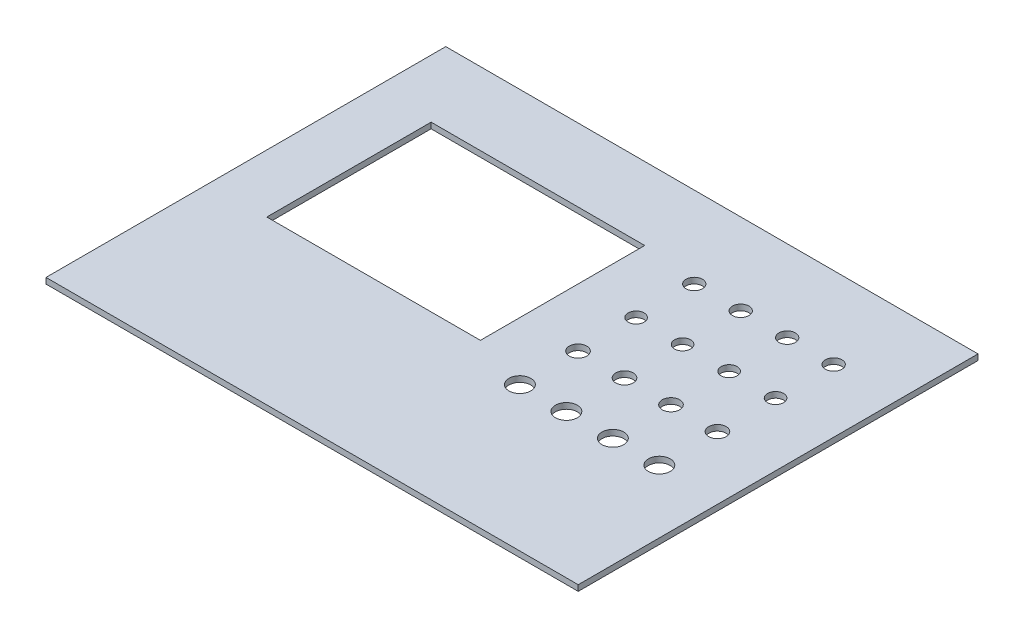
SolidWorks part; units mm, degrees
ref_plane "Front Plane" through (0, 0, 0) normal (0, 0, 1) x (1, 0, 0)
ref_plane "Top Plane" through (0, 0, 0) normal (0, 1, 0) x (1, 0, 0)
ref_plane "Right Plane" through (0, 0, 0) normal (1, 0, 0) x (0, 0, -1)
sketch "Sketch1" plane through (0, 0, 0) normal (0, 1, 0) x (1, 0, 0)
  line L1 (0, 0) -> (581.66, 0)
  line L2 (0, 0) -> (0, 436.88)
  line L3 (0, 436.88) -> (581.66, 436.88)
  line L4 (581.66, 0) -> (581.66, 436.88)
  dimension "D1" = 581.66
  dimension "D2" = 436.88
extrude "Boss-Extrude1" add sketch "Sketch1" along normal blind 6.35
sketch "Sketch3" plane through (0, 6.35, 0) normal (0, 1, 0) x (1, 0, 0)
  line L0 (0, 0) -> (581.66, 0) construction
  line L1 (63.5, 357.378) -> (296.926, 357.378)
  line L2 (63.5, 357.378) -> (63.5, 177.8)
  line L3 (63.5, 177.8) -> (296.926, 177.8)
  line L4 (296.926, 357.378) -> (296.926, 177.8)
  line L5 (0, 436.88) -> (0, 0) construction
  point P4 (180.213, 177.8)
  point P7 (63.5, 267.589)
  dimension "D1" = 233.426
  dimension "D2" = 179.578
  dimension "D3" = 177.8
  dimension "D4" = 63.5
extrude "Cut-Extrude2" cut sketch "Sketch3" against normal through all
sketch "Sketch4" plane through (0, 6.35, 0) normal (0, 1, 0) x (1, 0, 0)
  line L0 (296.926, 177.8) -> (296.926, 357.378) construction
  line L1 (581.66, 436.88) -> (0, 436.88) construction
  circle A0 centre (360.426, 347.98) radius 9.017
  circle A1 centre (411.226, 347.98) radius 9.017
  circle A2 centre (462.026, 347.98) radius 9.017
  circle A3 centre (512.826, 347.98) radius 9.017
  dimension "D1" = 18.034
  dimension "D3" = 63.5
  dimension "D4" = 88.9
  dimension "D5" = 50.8
  dimension "D2" = 4
extrude "Cut-Extrude3" cut sketch "Sketch4" against normal through all
sketch "Sketch5" plane through (0, 6.35, 0) normal (0, 1, 0) x (1, 0, 0)
  line L0 (296.926, 177.8) -> (296.926, 357.378) construction
  line L1 (581.66, 436.88) -> (0, 436.88) construction
  circle A0 centre (360.426, 284.48) radius 8.763
  circle A1 centre (411.226, 284.48) radius 8.763
  circle A2 centre (462.026, 284.48) radius 8.763
  circle A3 centre (512.826, 284.48) radius 8.763
  dimension "D1" = 17.526
  dimension "D3" = 63.5
  dimension "D4" = 152.4
  dimension "D5" = 50.8
  dimension "D2" = 4
extrude "Cut-Extrude4" cut sketch "Sketch5" against normal through all
sketch "Sketch6" plane through (0, 6.35, 0) normal (0, 1, 0) x (1, 0, 0)
  line L0 (296.926, 177.8) -> (296.926, 357.378) construction
  line L1 (581.66, 436.88) -> (0, 436.88) construction
  circle A0 centre (360.426, 220.98) radius 9.525
  circle A1 centre (411.226, 220.98) radius 9.525
  circle A2 centre (462.026, 220.98) radius 9.525
  circle A3 centre (512.826, 220.98) radius 9.525
  dimension "D1" = 19.05
  dimension "D3" = 63.5
  dimension "D4" = 215.9
  dimension "D5" = 50.8
  dimension "D2" = 4
extrude "Cut-Extrude5" cut sketch "Sketch6" against normal through all
sketch "Sketch7" plane through (0, 6.35, 0) normal (0, 1, 0) x (1, 0, 0)
  line L4 (296.926, 177.8) -> (296.926, 357.378) construction
  line L5 (581.66, 436.88) -> (0, 436.88) construction
  circle A0 centre (360.426, 157.48) radius 11.938
  circle A1 centre (411.226, 157.48) radius 11.938
  circle A2 centre (462.026, 157.48) radius 11.938
  circle A3 centre (512.826, 157.48) radius 11.938
  point P12 (329.8182, 230.4174)
  dimension "D3" = 23.876
  dimension "D2" = 63.5
  dimension "D4" = 279.4
  dimension "D5" = 50.8
  dimension "D1" = 4
extrude "Cut-Extrude6" cut sketch "Sketch7" against normal through all
